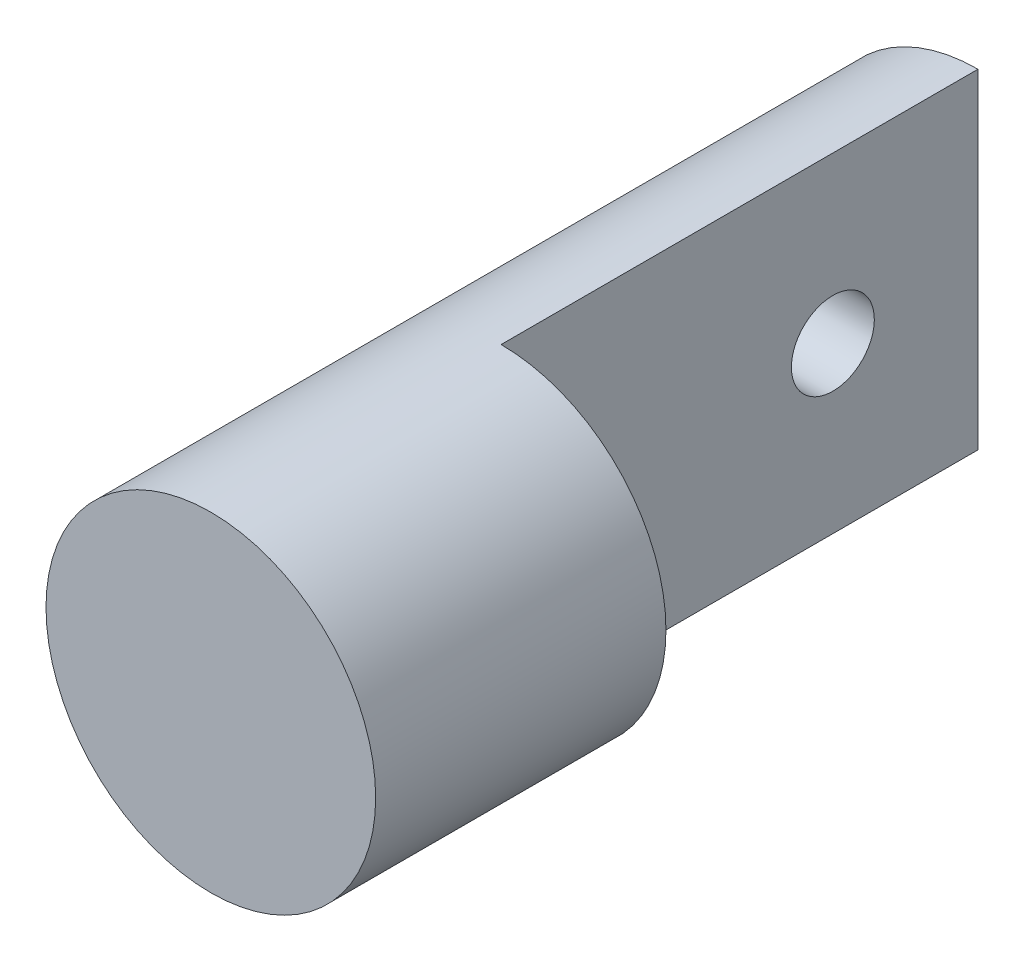
SolidWorks part; units mm, degrees
material "2024-T3"
ref_plane "正面" through (0, 0, 0) normal (0, 0, 1) x (1, 0, 0)
ref_plane "平面" through (0, 0, 0) normal (0, 1, 0) x (1, 0, 0)
ref_plane "右側面" through (0, 0, 0) normal (1, 0, 0) x (0, 0, -1)
sketch "ｽｹｯﾁ1" plane through (0, 0, 0) normal (0, 0, 1) x (1, 0, 0)
  circle A0 centre (0, 0) radius 7.95
  dimension "D1" = 15.9
extrude "ﾎﾞｽ - 押し出し1" add sketch "ｽｹｯﾁ1" along normal blind 30
sketch "ｽｹｯﾁ2" plane through (0, 0, 30) normal (0, 0, 1) x (1, 0, 0)
  circle A0 centre (0, 0) radius 7.95
  dimension "D1" = 15.9
extrude "ﾎﾞｽ - 押し出し2" add sketch "ｽｹｯﾁ2" along normal blind 10
sketch "ｽｹｯﾁ3" plane through (0, 0, 0) normal (0, 0, -1) x (-1, 0, 0)
  line L0 (0, 0) -> (7.95, 0)
  line L2 (-7.95, 7.95) -> (0, 7.95)
  line L3 (-7.95, 7.95) -> (-7.95, -7.95)
  line L4 (-7.95, -7.95) -> (0, -7.95)
  line L5 (0, 7.95) -> (0, -7.95)
  circle A0 centre (0, 0) radius 7.95 construction
  dimension "D1" = 7.95
extrude "ｶｯﾄ - 押し出し1" cut sketch "ｽｹｯﾁ3" against normal blind 26 contours L5 L4 L3 L2
sketch "ｽｹｯﾁ4" plane through (0, 0, 0) normal (1, 0, 0) x (0, 0, -1)
  line L0 (-26, 7.95) -> (-26, -7.95) construction
  line L1 (0, 7.95) -> (-26, 7.95) construction
  circle A0 centre (-10, 0) radius 2
  point P0 (-10, 0)
  dimension "D3" = 4
  dimension "D1" = 16
  dimension "D2" = 7.95
extrude "ｶｯﾄ - 押し出し2" cut sketch "ｽｹｯﾁ4" against normal through all contours A0
sketch "ｽｹｯﾁ5" plane through (0, 0, 0) normal (0, 0, -1) x (-1, 0, 0)
  line L0 (0, 0) -> (7.95, 0)
  arc A0 (0, -7.95) -> (0, 7.95) centre (0, 0) ccw construction
  point P0 (3.95, 0)
  dimension "D1" = 4
hole_wizard "M3x0.5 ねじ穴1" positions "ｽｹｯﾁ5" profile "ｽｹｯﾁ6" tap size "M3x0.5" standard "JIS"
sketch "ｽｹｯﾁ6" plane through (-3.95, 0, 0) normal (1, 0, 0) x (0, 1, 0)
  line L0 (0, 0) -> (0, 8)
  line L1 (0, 8) -> (1.25, 8)
  line L2 (1.25, 8) -> (1.25, 0)
  line L5 (1.25, 0) -> (0, 0)
  line L11 (0, -6.35) -> (0, 107.95) construction
  dimension "次ｻｰﾌｪｽまでのねじ下穴ﾄﾞﾘﾙ直径" = 2.5
  dimension "次ｻｰﾌｪｽまでのねじ下穴ﾄﾞﾘﾙの深さ" = 8
cosmetic thread "穴のねじ山1" parameters "D2"=3
ref_plane "平面1" through (0, 0, 3) normal (0, 0, -1) x (-1, 0, 0)
sketch "ｽｹｯﾁ7" plane through (0, 0, 3) normal (0, 0, -1) x (-1, 0, 0)
  line L1 (0, 7.95) -> (0, -7.95)
  line L2 (0, 7.95) -> (0, -7.95)
  arc A1 (0, -7.95) -> (0, 7.95) centre (0, 0) ccw
  arc A2 (0, -7.95) -> (0, 7.95) centre (0, 0) ccw
  dimension "D1" = 0
extrude "ｶｯﾄ - 押し出し3" cut sketch "ｽｹｯﾁ7" along normal through all
